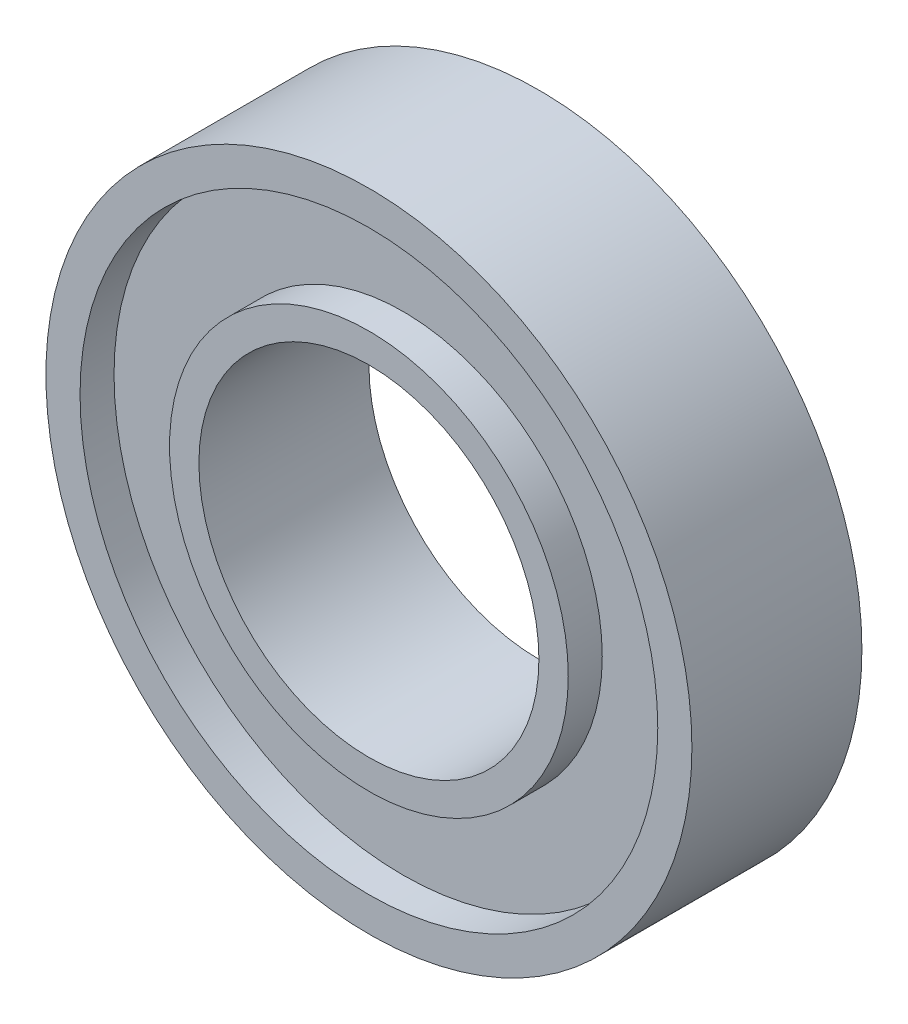
SolidWorks part; units mm, degrees
ref_plane "前视基准面" through (0, 0, 0) normal (0, 0, 1) x (1, 0, 0)
ref_plane "上视基准面" through (0, 0, 0) normal (0, 1, 0) x (1, 0, 0)
ref_plane "右视基准面" through (0, 0, 0) normal (1, 0, 0) x (0, 0, -1)
sketch "草图1" plane through (0, 0, 0) normal (0, 0, 1) x (1, 0, 0)
  circle A0 centre (0, 0) radius 5
  circle A1 centre (0, 0) radius 9.5
  dimension "D1" = 10
  dimension "D2" = 19
extrude "凸台-拉伸1" add sketch "草图1" along normal blind 5
sketch "草图2" plane through (0, 0, 5) normal (0, 0, 1) x (1, 0, 0)
  circle A0 centre (0, 0) radius 5.8634
  circle A1 centre (0, 0) radius 8.4962
extrude "切除-拉伸1" cut sketch "草图2" against normal blind 1
ref_plane "基准面4" through (0, 0, 2.5) normal (0, 0, 1) x (1, 0, 0)
mirror "镜向2" about plane through (0, 0, 2.5) normal (0, 0, 1) of "切除-拉伸1"
